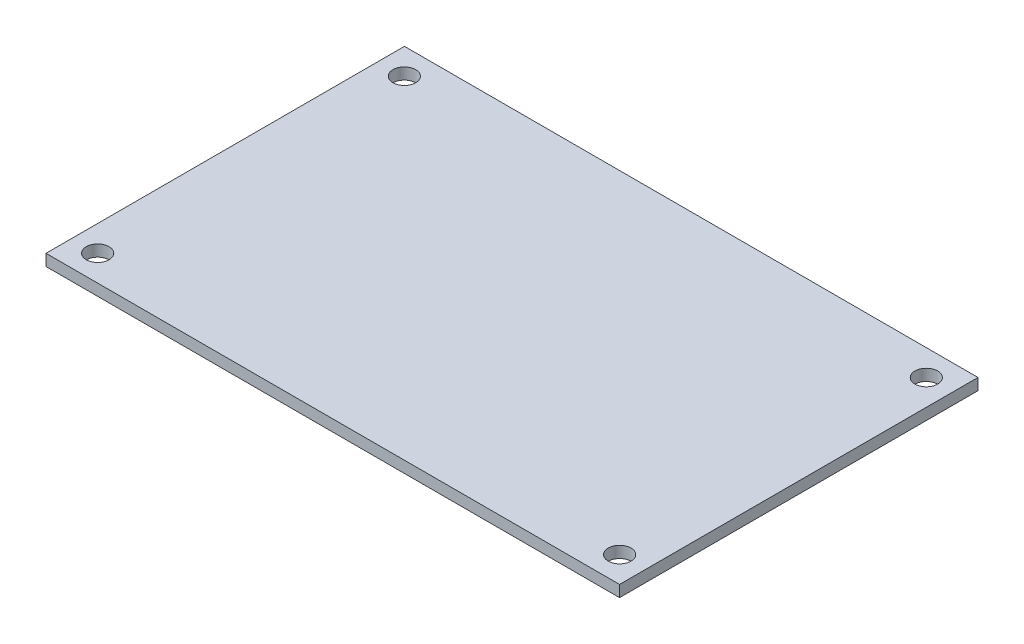
SolidWorks part; units mm, degrees
ref_plane "Front Plane" through (0, 0, 0) normal (0, 0, 1) x (1, 0, 0)
ref_plane "Top Plane" through (0, 0, 0) normal (0, 1, 0) x (1, 0, 0)
ref_plane "Right Plane" through (0, 0, 0) normal (1, 0, 0) x (0, 0, -1)
sketch "Sketch1" plane through (0, 0, 0) normal (0, 1, 0) x (1, 0, 0)
  line L1 (-40, 25) -> (40, 25)
  line L2 (-40, 25) -> (-40, -25)
  line L3 (-40, -25) -> (40, -25)
  line L4 (40, 25) -> (40, -25)
  line L5 (-40, 25) -> (40, -25) construction
  line L6 (-40, -25) -> (40, 25) construction
  point P0 (0, 0)
  dimension "D1" = 50
  dimension "D2" = 80
extrude "Boss-Extrude1" add sketch "Sketch1" along normal mid plane 1.6002
sketch "Sketch2" plane through (0, 0.8001, 0) normal (0, 1, 0) x (1, 0, 0)
  line L1 (-36.4028, -21.3874) -> (36.4028, -21.3874) construction
  line L2 (-36.4028, -21.3874) -> (-36.4028, 21.3874) construction
  line L3 (-36.4028, 21.3874) -> (36.4028, 21.3874) construction
  line L4 (36.4028, -21.3874) -> (36.4028, 21.3874) construction
  line L5 (-36.4028, -21.3874) -> (36.4028, 21.3874) construction
  line L6 (-36.4028, 21.3874) -> (36.4028, -21.3874) construction
  circle A0 centre (-36.4028, 21.3874) radius 1.5875
  circle A1 centre (-36.4028, -21.3874) radius 1.5875
  circle A2 centre (36.4028, -21.3874) radius 1.5875
  circle A3 centre (36.4028, 21.3874) radius 1.5875
  point P0 (0, 0)
  point P10 (-46.1673, 26.8818)
  point P11 (-46.1673, 26.3655)
  point P12 (-36.4028, 21.3874)
  dimension "D1" = 3.175
extrude "Cut-Extrude1" cut sketch "Sketch2" against normal through all
